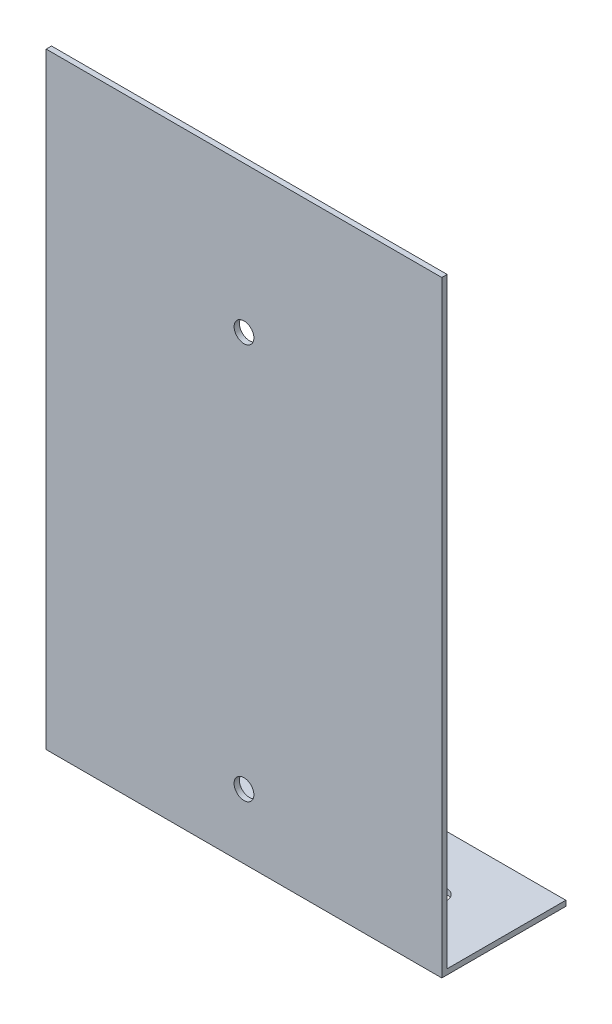
SolidWorks part; units mm, degrees
ref_plane "Front Plane" through (0, 0, 0) normal (0, 0, 1) x (1, 0, 0)
ref_plane "Top Plane" through (0, 0, 0) normal (0, 1, 0) x (1, 0, 0)
ref_plane "Right Plane" through (0, 0, 0) normal (1, 0, 0) x (0, 0, -1)
sketch "Sketch1" plane through (0, 0, 0) normal (0, 1, 0) x (1, 0, 0)
  line L0 (0, 30) -> (35, 30) construction
  line L1 (0, 60) -> (200, 60)
  line L2 (0, 60) -> (0, 0)
  line L3 (0, 0) -> (200, 0)
  line L4 (200, 60) -> (200, 0)
  line L5 (165, 30) -> (200, 30) construction
  circle A1 centre (35, 30) radius 5
  circle A2 centre (165, 30) radius 5
  dimension "D3" = 10
  dimension "D4" = 10
  dimension "D1" = 60
  dimension "D2" = 200
  dimension "D5" = 35
  dimension "D6" = 35
extrude "Boss-Extrude1" add sketch "Sketch1" along normal blind 2.7
sketch "Sketch2" plane through (0, 0, 0) normal (0, 0, 1) x (1, 0, 0)
  line L0 (100, 2.7) -> (100, 32.7) construction
  line L1 (0, 0) -> (200, 0)
  line L2 (0, 0) -> (0, 306.7)
  line L3 (0, 306.7) -> (200, 306.7)
  line L4 (200, 0) -> (200, 306.7)
  line L5 (0, 2.7) -> (200, 2.7) construction
  line L6 (100, 2.7) -> (100, 232.7) construction
  circle A0 centre (100, 32.7) radius 5
  circle A1 centre (100, 232.7) radius 5
  point P12 (0, 0)
  point P14 (0, 0)
  point P15 (100, 0)
  dimension "D4" = 10
  dimension "D6" = 10
  dimension "D1" = 306.7
  dimension "D2" = 200
  dimension "D3" = 30
  dimension "D5" = 230
extrude "Boss-Extrude2" add sketch "Sketch2" along normal blind 2.7
